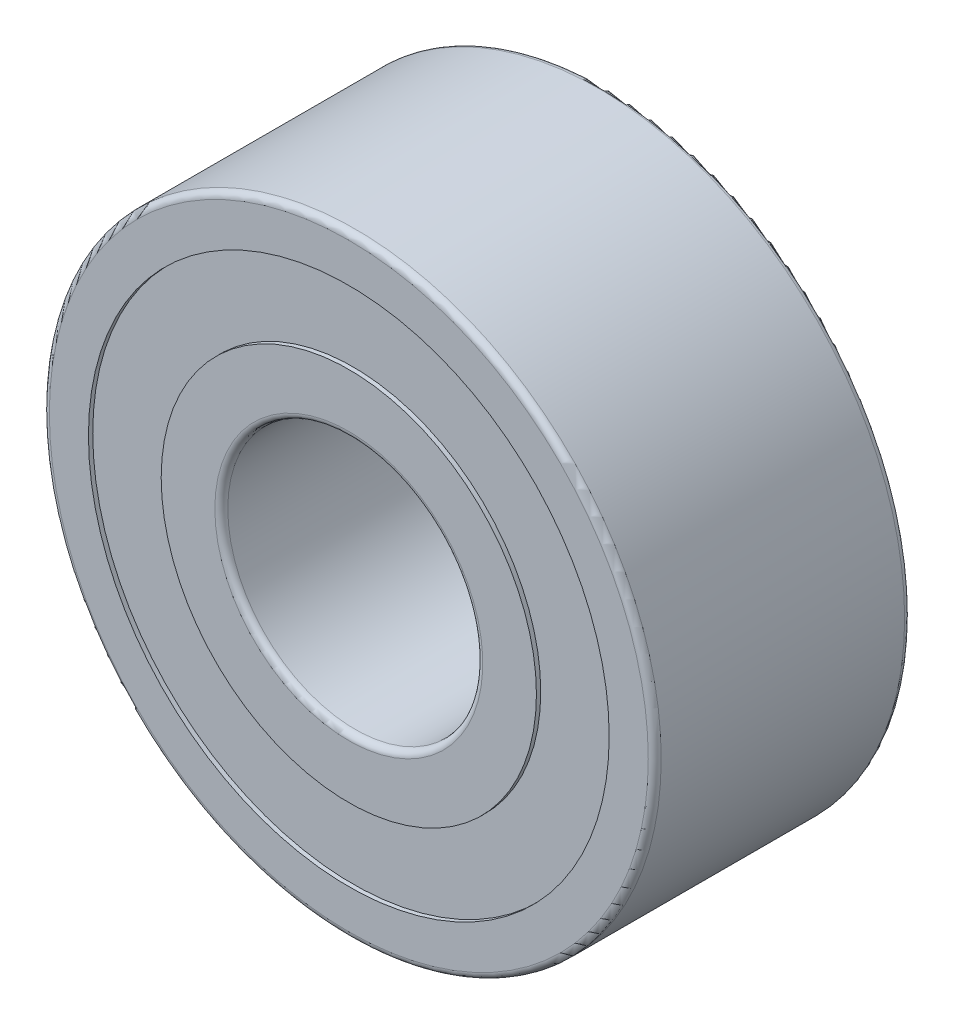
SolidWorks part; units mm, degrees
material "Chrome Stainless Steel"
ref_plane "Front Plane" through (0, 0, 0) normal (0, 0, 1) x (1, 0, 0)
ref_plane "Top Plane" through (0, 0, 0) normal (0, 1, 0) x (1, 0, 0)
ref_plane "Right Plane" through (0, 0, 0) normal (1, 0, 0) x (0, 0, -1)
sketch "Sketch2" plane through (0, 0, 0) normal (1, 0, 0) x (0, 0, -1)
  line L0 (15.0813, 15) -> (15.0812, 22.0726)
  line L1 (15.0812, 22.0726) -> (11.4807, 22.0726)
  line L2 (4.3943, 22.0726) -> (-4.3943, 22.0726)
  line L3 (15.0813, 15) -> (-15.0812, 15)
  line L4 (0, 0) -> (0, 35.9918) construction
  line L5 (-15.0812, 22.0726) -> (-11.4807, 22.0726)
  line L6 (-15.0812, 15) -> (-15.0812, 22.0726)
  line L7 (15.0812, 30.6324) -> (15.0812, 35.9918)
  line L8 (15.0812, 35.9918) -> (-15.0812, 35.9918)
  line L9 (15.0812, 30.6324) -> (11.4807, 30.6324)
  line L10 (-4.3943, 30.6324) -> (4.3943, 30.6324)
  line L11 (-15.0812, 30.6324) -> (-15.0812, 35.9918)
  line L12 (-15.0812, 30.6324) -> (-11.4807, 30.6324)
  line L13 (0, 0) -> (53.3259, 0) construction
  line L14 (15.0812, 22.0726) -> (15.0812, 30.6324) construction
  arc A0 (11.4807, 22.0726) -> (4.3943, 22.0726) centre (7.9375, 26.3525) cw
  arc A1 (-11.4807, 22.0726) -> (-4.3943, 22.0726) centre (-7.9375, 26.3525) ccw
  arc A2 (4.3943, 30.6324) -> (11.4807, 30.6324) centre (7.9375, 26.3525) cw
  arc A3 (-4.3943, 30.6324) -> (-11.4807, 30.6324) centre (-7.9375, 26.3525) ccw
  point P5 (15.0812, 26.3525)
  point P11 (0, 22.0726)
  point P15 (0, 15)
  point P26 (0, 30.6324)
  dimension "D2" = 5.5562
  dimension "D1" = 30.1625
  dimension "D3" = 15.875
  dimension "D4" = 30
  dimension "D5" = 61.2648
  dimension "D6" = 71.9836
  dimension "D7" = 44.1452
revolve "Revolve1" add sketch "Sketch2" angle 360 about L13
sketch "Sketch3" plane through (0, 0, 0) normal (1, 0, 0) x (0, 0, -1)
  line L0 (7.9375, 26.3525) -> (7.9375, 31.9088) construction
  line L1 (7.9375, 31.9088) -> (7.9375, 20.7962)
  arc A0 (11.4807, 30.6324) -> (4.3943, 30.6324) centre (7.9375, 26.3525) ccw construction
  arc A1 (7.9375, 31.9088) -> (7.9375, 20.7962) centre (7.9375, 26.3525) cw
  arc A2 (4.3943, 22.0726) -> (11.4807, 22.0726) centre (7.9375, 26.3525) ccw construction
revolve "Revolve2" add sketch "Sketch3" angle 360 about L0
sketch "Sketch4" plane through (0, 0, 0) normal (1, 0, 0) x (0, 0, -1)
  line L0 (-7.9375, 31.9088) -> (-7.9375, 26.3525) construction
  line L1 (-7.9375, 31.9088) -> (-7.9375, 20.7962)
  arc A0 (-4.3943, 30.6324) -> (-11.4807, 30.6324) centre (-7.9375, 26.3525) ccw construction
  arc A1 (-7.9375, 31.9088) -> (-7.9375, 20.7962) centre (-7.9375, 26.3525) ccw
  arc A2 (-11.4807, 22.0726) -> (-4.3943, 22.0726) centre (-7.9375, 26.3525) ccw construction
revolve "Revolve3" add sketch "Sketch4" angle 360 about L0
pattern_circular "CirPattern1" count 8 over 360 about axis through (0, 0, 0) along (0, 0, 1) of bodies 111 103
sketch "Sketch5" plane through (0, 0, 0) normal (1, 0, 0) x (0, 0, -1)
  line L0 (15.0812, 30.6324) -> (11.4807, 30.6324) construction
  line L1 (14.5732, 22.0726) -> (13.8112, 22.0726)
  line L2 (14.5732, 22.0726) -> (14.5732, 30.6324)
  line L3 (14.5732, 30.6324) -> (13.8112, 30.6324)
  line L4 (13.8112, 22.0726) -> (13.8112, 30.6324)
  line L5 (14.5732, 22.0726) -> (13.8112, 30.6324) construction
  line L6 (14.5732, 30.6324) -> (13.8112, 22.0726) construction
  line L7 (15.0812, 22.0726) -> (11.4807, 22.0726) construction
  line L8 (0, 0) -> (0, 35.9918) construction
  line L9 (-13.8112, 22.0726) -> (-13.8112, 30.6324)
  line L10 (-14.5732, 22.0726) -> (-13.8112, 22.0726)
  line L11 (-14.5732, 22.0726) -> (-14.5732, 30.6324)
  line L12 (-14.5732, 30.6324) -> (-13.8112, 30.6324)
  line L13 (0, 0) -> (-24.7191, 0) construction
  line L14 (15.0812, -22.0726) -> (15.0812, 22.0726) construction
  point P0 (14.1922, 26.3525)
  dimension "D1" = 0.762
  dimension "D2" = 0.508
revolve "Revolve4" add sketch "Sketch5" angle 360 about L13
fillet "Fillet1" radius 0.762 2 edges at (35.9918, 0, 15.0812) (35.9918, 0, -15.0812)
fillet "Fillet2" radius 0.762 2 edges at (15, 0, -15.0813) (15, 0, 15.0812)
